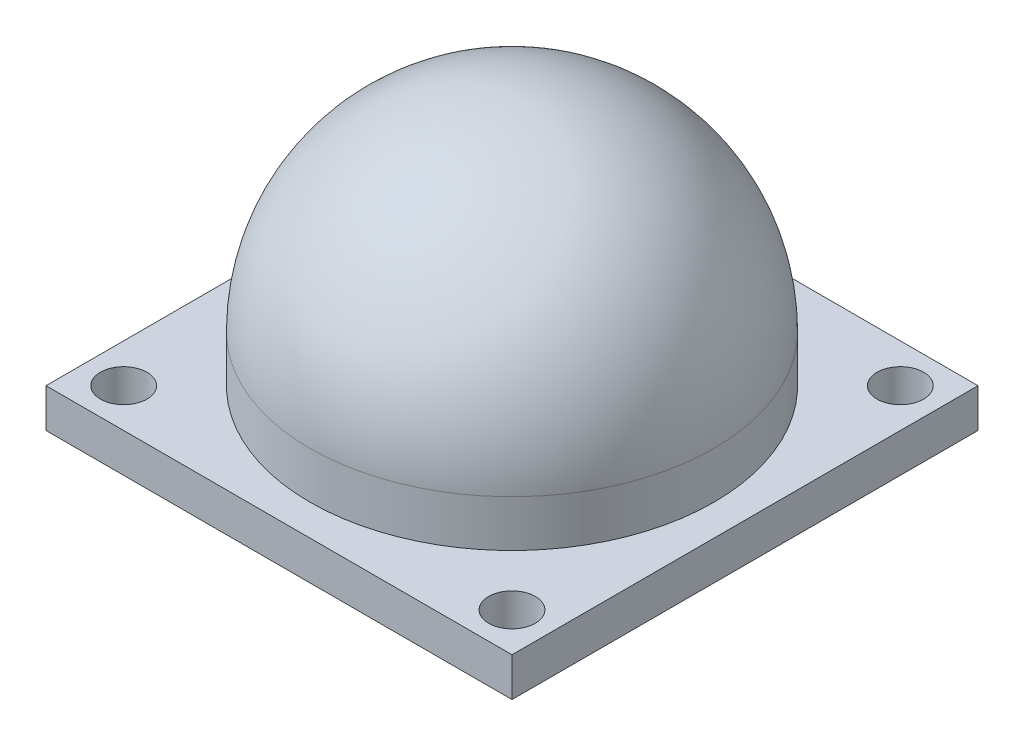
SolidWorks part; units mm, degrees
ref_plane "Спереди" through (0, 0, 0) normal (0, 0, 1) x (1, 0, 0)
ref_plane "Сверху" through (0, 0, 0) normal (0, 1, 0) x (1, 0, 0)
ref_plane "Справа" through (0, 0, 0) normal (1, 0, 0) x (0, 0, -1)
other "Configuration Table"
sketch "Эскиз1" plane through (0, 0, 0) normal (0, 1, 0) x (1, 0, 0)
  line L1 (15, -15) -> (-15, -15)
  line L2 (15, -15) -> (15, 15)
  line L3 (15, 15) -> (-15, 15)
  line L4 (-15, -15) -> (-15, 15)
  line L5 (15, -15) -> (-15, 15) construction
  line L6 (15, 15) -> (-15, -15) construction
  line L11 (12.5, -12.5) -> (-12.5, 12.5) construction
  line L12 (12.5, 12.5) -> (-12.5, -12.5) construction
  circle A0 centre (-12.5, 12.5) radius 1.5
  circle A1 centre (12.5, 12.5) radius 1.5
  circle A2 centre (-12.5, -12.5) radius 1.5
  circle A4 centre (12.5, -12.5) radius 1.5
  point P0 (0, 0)
  point P6 (0, 0)
extrude "Бобышка-Вытянуть1" add sketch "Эскиз1" along normal blind 2.5
sketch "Эскиз2" plane through (0, 2.5, 0) normal (0, 1, 0) x (1, 0, 0)
  circle A0 centre (0, 0) radius 13
extrude "Бобышка-Вытянуть2" add sketch "Эскиз2" along normal blind 3
sketch "Эскиз3" plane through (0, 5.5, 0) normal (0, 1, 0) x (1, 0, 0)
  line L0 (0, 13) -> (0, -13)
  line L1 (0, 13) -> (0, 20.0949) construction
  arc A0 (0, 13) -> (0, -13) centre (0, 0) ccw
  circle A1 centre (0, 0) radius 13 construction
revolve "Повернуть1" add sketch "Эскиз3" angle 180 about L1
